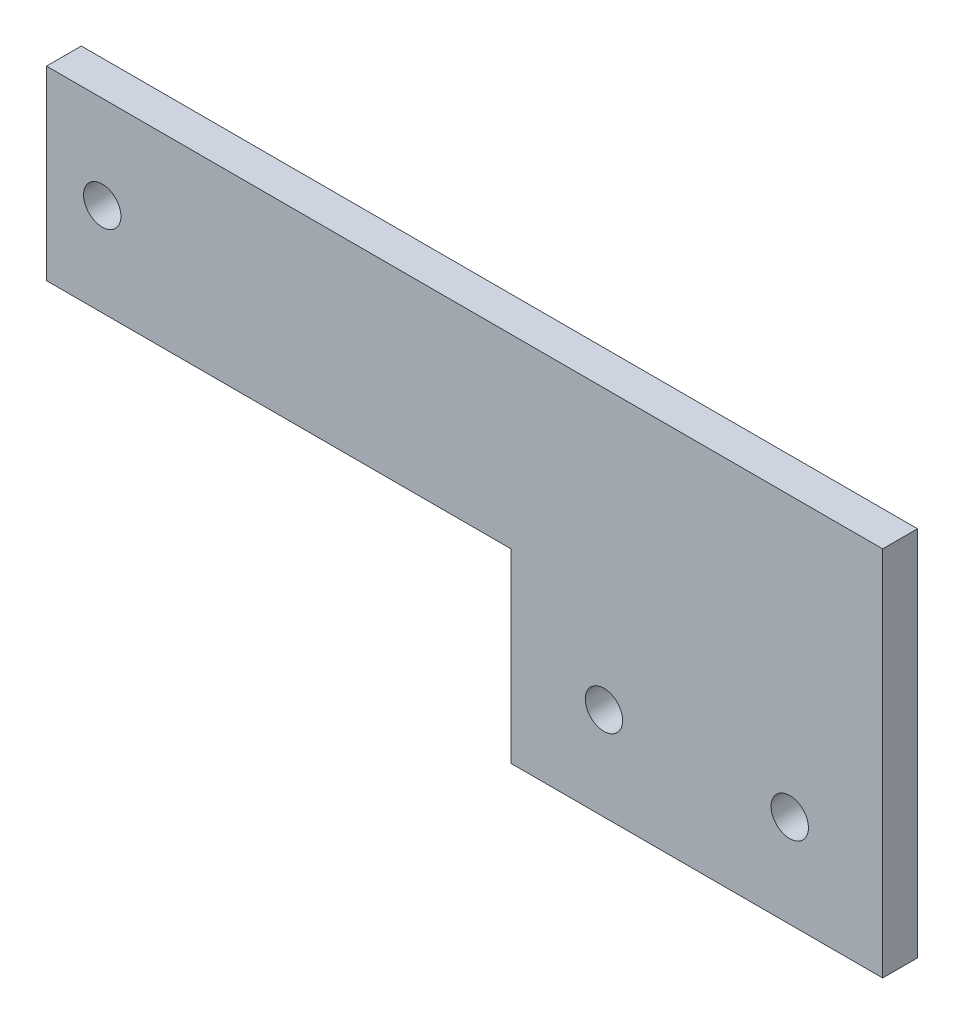
SolidWorks part; units mm, degrees
ref_plane "Front Plane" through (0, 0, 0) normal (0, 0, 1) x (1, 0, 0)
ref_plane "Top Plane" through (0, 0, 0) normal (0, 1, 0) x (1, 0, 0)
ref_plane "Right Plane" through (0, 0, 0) normal (1, 0, 0) x (0, 0, -1)
sketch "Sketch1" plane through (0, 0, 0) normal (0, 0, 1) x (1, 0, 0)
  line L0 (0, 50.8) -> (-63.5, 50.8)
  line L1 (0, 0) -> (50.8, 0)
  line L2 (0, 0) -> (0, 50.8)
  line L3 (0, 50.8) -> (50.8, 50.8)
  line L4 (50.8, 0) -> (50.8, 50.8)
  line L5 (-63.5, 50.8) -> (-63.5, 25.4)
  line L6 (-63.5, 25.4) -> (0, 25.4)
  line L7 (-55.88, 50.8) -> (-55.88, 38.1) construction
  line L8 (-55.88, 38.1) -> (-44.8815, 44.45) construction
  circle A0 centre (12.7, 12.7) radius 2.5527
  circle A1 centre (38.1, 12.7) radius 2.5527
  circle A2 centre (-55.88, 38.1) radius 2.5527
  dimension "D3" = 5.1054
  dimension "D11" = 5.1054
  dimension "D1" = 50.8
  dimension "D2" = 50.8
  dimension "D4" = 12.7
  dimension "D5" = 12.7
  dimension "D6" = 25.4
  dimension "D7" = 25.4
  dimension "D8" = 63.5
  dimension "D9" = 12.7
  dimension "D12" = 7.62
  dimension "D13" = 60
extrude "Boss-Extrude1" add sketch "Sketch1" along normal blind 4.7625
